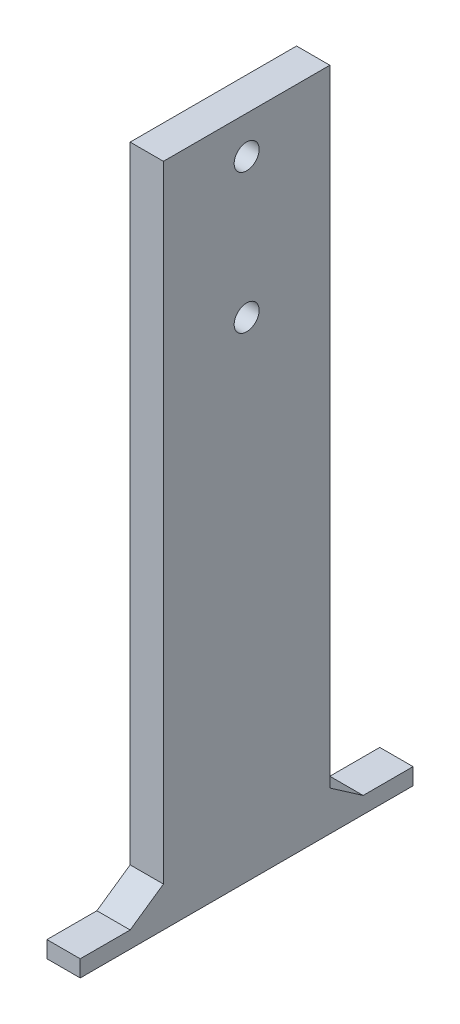
SolidWorks part; units mm, degrees
ref_plane "Front Plane" through (0, 0, 0) normal (0, 0, 1) x (1, 0, 0)
ref_plane "Top Plane" through (0, 0, 0) normal (0, 1, 0) x (1, 0, 0)
ref_plane "Right Plane" through (0, 0, 0) normal (1, 0, 0) x (0, 0, -1)
sketch "Sketch1" plane through (0, 0, 0) normal (0, 1, 0) x (1, 0, 0)
  line L1 (10, 0) -> (10, 50)
  line L2 (0, 0) -> (0, 50)
  line L4 (0, 50) -> (0, 75)
  line L5 (0, 153.69) -> (0, -246.31) construction
  line L6 (0, 75) -> (10, 75)
  line L7 (10, 75) -> (10, 50)
  line L8 (0, 0) -> (0, -25)
  line L9 (0, -25) -> (10, -25)
  line L10 (10, -25) -> (10, 0)
extrude "Boss-Extrude1" add sketch "Sketch1" along normal blind 200
sketch "Sketch2" plane through (10, 0, 0) normal (1, 0, 0) x (0, 0, -1)
  circle A1 centre (25, 188.7753) radius 3.75
  circle A2 centre (25, 146.8997) radius 3.75
extrude "Cut-Extrude1" cut sketch "Sketch2" against normal blind 10
sketch "Sketch3" plane through (0, 0, 0) normal (-1, 0, 0) x (0, 0, 1)
  line L0 (25, 200) -> (25, 5)
  line L2 (-75, 200) -> (25, 200) construction
  line L5 (0, 200) -> (25, 200)
  line L6 (-75, 200) -> (-75, 0) construction
  line L7 (-75, 5) -> (-60, 5)
  line L8 (-60, 5) -> (-50, 11.9378)
  line L9 (-50, 11.9378) -> (-50, 200)
  line L10 (-50, 200) -> (-75, 200)
  line L11 (-75, 200) -> (-75, 5)
  line L12 (0, 11.9378) -> (0, 200)
  line L13 (10, 5) -> (0, 11.9378)
  line L14 (25, 5) -> (10, 5)
extrude "Cut-Extrude2" cut sketch "Sketch3" against normal blind 10
